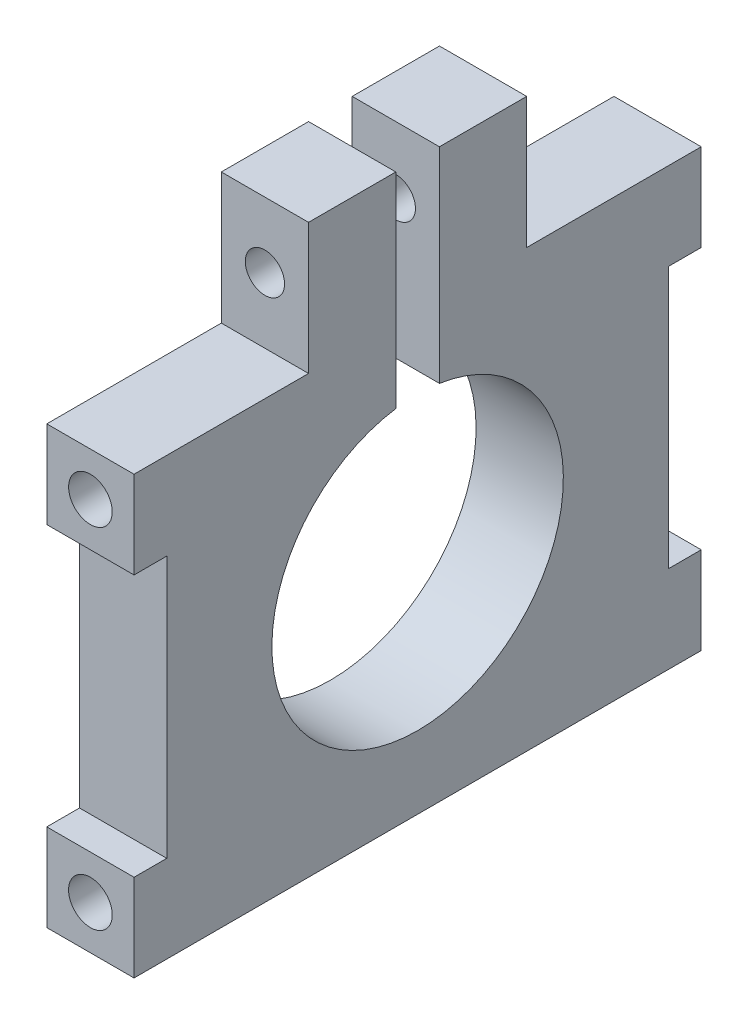
SolidWorks part; units mm, degrees
material "ABS"
ref_plane "Alzado" through (0, 0, 0) normal (0, 0, 1) x (1, 0, 0)
ref_plane "Planta" through (0, 0, 0) normal (0, 1, 0) x (1, 0, 0)
ref_plane "Vista lateral" through (0, 0, 0) normal (1, 0, 0) x (0, 0, -1)
sketch "Croquis1" plane through (0, 0, 0) normal (1, 0, 0) x (0, 0, -1)
  line L1 (-32.5, -25) -> (32.5, -25)
  line L2 (-32.5, -25) -> (-32.5, 25)
  line L3 (-32.5, 25) -> (32.5, 25)
  line L4 (32.5, -25) -> (32.5, 25)
  line L5 (-32.5, -25) -> (32.5, 25) construction
  line L6 (-32.5, 25) -> (32.5, -25) construction
  circle A0 centre (0, 0) radius 16.7005
  dimension "D1" = 33.401
  dimension "D2" = 65
  dimension "D3" = 50
extrude "Saliente-Extruir1" add sketch "Croquis1" along normal mid plane 10
sketch "Croquis2" plane through (5, 0, 0) normal (1, 0, 0) x (0, 0, -1)
  line L0 (-32.5, 25) -> (-32.5, -25) construction
  line L1 (-36.25, -15) -> (-28.75, -15)
  line L2 (-36.25, -15) -> (-36.25, 15)
  line L3 (-36.25, 15) -> (-28.75, 15)
  line L4 (-28.75, -15) -> (-28.75, 15)
  line L5 (-36.25, -15) -> (-28.75, 15) construction
  line L6 (-36.25, 15) -> (-28.75, -15) construction
  line L7 (32.5, 25) -> (-32.5, 25) construction
  line L8 (0, 5.5) -> (0, -5.5) construction
  line L9 (36.25, 15) -> (28.75, 15)
  line L10 (28.75, -15) -> (28.75, 15)
  line L11 (36.25, -15) -> (28.75, -15)
  line L12 (36.25, -15) -> (36.25, 15)
  point P0 (-32.5, 0)
  dimension "D1" = 10
  dimension "D2" = 7.5
extrude "Cortar-Extruir1" cut sketch "Croquis2" against normal through all
sketch "Croquis3" plane through (5, 0, 0) normal (1, 0, 0) x (0, 0, -1)
  line L0 (0, 16.7005) -> (0, 25) construction
  line L1 (32.5, 25) -> (-32.5, 25) construction
  line L3 (-2.5, 13.3503) -> (2.5, 13.3503)
  line L4 (-2.5, 13.3503) -> (-2.5, 28.3502)
  line L5 (-2.5, 28.3502) -> (2.5, 28.3502)
  line L6 (2.5, 13.3503) -> (2.5, 28.3502)
  line L7 (-2.5, 13.3503) -> (2.5, 28.3502) construction
  line L8 (-2.5, 28.3502) -> (2.5, 13.3503) construction
  circle A0 centre (0, 0) radius 16.7005 construction
  point P6 (0, 20.8502)
  dimension "D1" = 5
  dimension "D2" = 15
extrude "Cortar-Extruir2" cut sketch "Croquis3" against normal through all
sketch "Croquis4" plane through (5, 0, 0) normal (1, 0, 0) x (0, 0, -1)
  line L0 (-2.5, 25) -> (-2.5, 40)
  line L1 (-2.5, 40) -> (-12.5, 40)
  line L2 (-12.5, 40) -> (-12.5, 25)
  line L3 (-2.5, 25) -> (-32.5, 25) construction
  line L4 (-12.5, 25) -> (-2.5, 25)
  line L5 (0, 5.5) -> (0, -5.5) construction
  line L6 (12.5, 40) -> (12.5, 25)
  line L7 (2.5, 40) -> (12.5, 40)
  line L8 (2.5, 25) -> (2.5, 40)
  line L9 (12.5, 25) -> (2.5, 25)
  dimension "D1" = 10
  dimension "D2" = 15
extrude "Saliente-Extruir2" add sketch "Croquis4" against normal up to surface (10 mm away) up to face at (-5, 3.1132, 0)
sketch "Croquis5" plane through (0, 0, 32.5) normal (0, 0, 1) x (1, 0, 0)
  line L0 (0, 25) -> (0, 15) construction
  line L1 (5, 25) -> (-5, 25) construction
  line L2 (-5, 15) -> (5, 15) construction
  line L3 (5.5, 0) -> (-5.5, 0) construction
  circle A0 centre (0, 20) radius 2.5
  circle A1 centre (0, -20) radius 2.5
  dimension "D1" = 5
extrude "Cortar-Extruir3" cut sketch "Croquis5" against normal blind 10
mirror "Simetría1" about plane through (0, 0, 0) normal (0, 0, 1) of "Cortar-Extruir3"
sketch "Croquis6" plane through (0, 0, 12.5) normal (0, 0, 1) x (1, 0, 0)
  line L0 (-5, 32.5) -> (5, 32.5) construction
  line L1 (-5, 40) -> (-5, 25) construction
  line L2 (5, 40) -> (5, 25) construction
  circle A0 centre (0, 32.5) radius 2.25
  dimension "D1" = 4.5
extrude "Cortar-Extruir4" cut sketch "Croquis6" against normal up to surface (25 mm away) up to face at (0, 32.5, -12.5)
